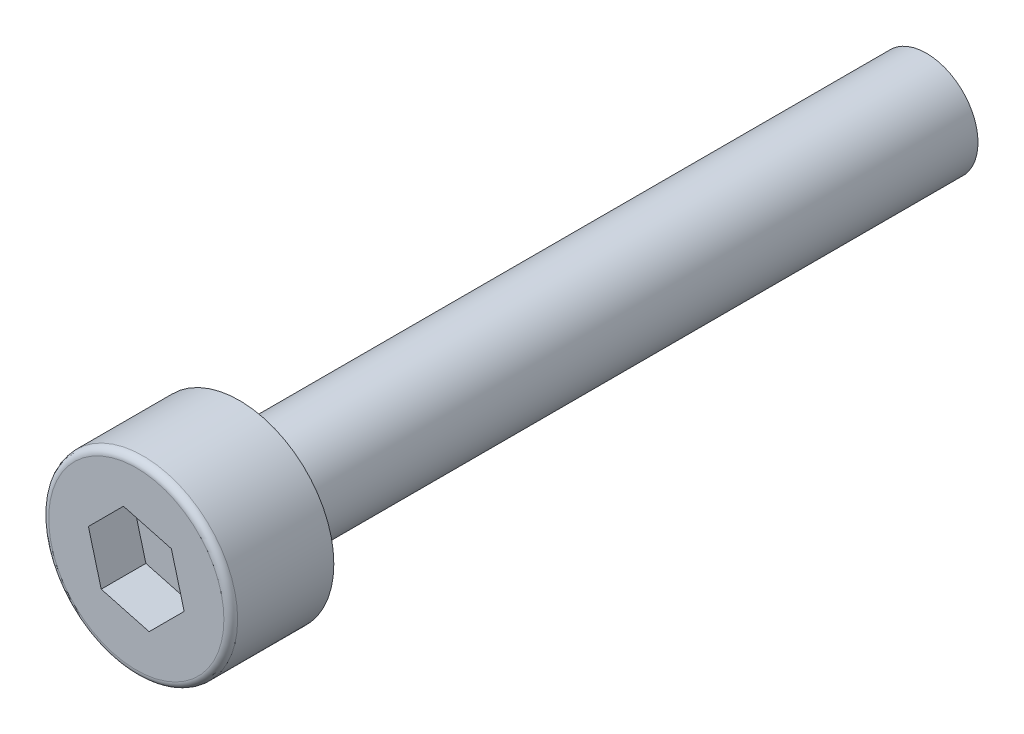
SolidWorks part; units mm, degrees
ref_plane "前视基准面" through (0, 0, 0) normal (0, 0, 1) x (1, 0, 0)
ref_plane "上视基准面" through (0, 0, 0) normal (0, 1, 0) x (1, 0, 0)
ref_plane "右视基准面" through (0, 0, 0) normal (1, 0, 0) x (0, 0, -1)
sketch "草图1" plane through (0, 0, 0) normal (0, 0, 1) x (1, 0, 0)
  circle A0 centre (0, 0) radius 2.75
  dimension "D1" = 5.5
extrude "凸台-拉伸1" add sketch "草图1" along normal blind 3
sketch "草图2" plane through (0, 0, 3) normal (0, 0, 1) x (1, 0, 0)
  line L1 (-1.0206, -1.0206) -> (0.3736, -1.3942)
  line L2 (0.3736, -1.3942) -> (1.3942, -0.3736)
  line L3 (1.3942, -0.3736) -> (1.0206, 1.0206)
  line L4 (1.0206, 1.0206) -> (-0.3736, 1.3942)
  line L5 (-0.3736, 1.3942) -> (-1.3942, 0.3736)
  line L6 (-1.3942, 0.3736) -> (-1.0206, -1.0206)
  circle A0 centre (0, 0) radius 1.25 construction
  dimension "D1" = 2.5
extrude "切除-拉伸1" cut sketch "草图2" against normal blind 1.3
sketch "草图3" plane through (0, 0, 0) normal (0, 0, -1) x (-1, 0, 0)
  circle A0 centre (0, 0) radius 1.5
  dimension "D1" = 3
extrude "凸台-拉伸2" add sketch "草图3" along normal blind 20
fillet "圆角1" radius 0.2 1 edges at (2.75, 0, 3)
